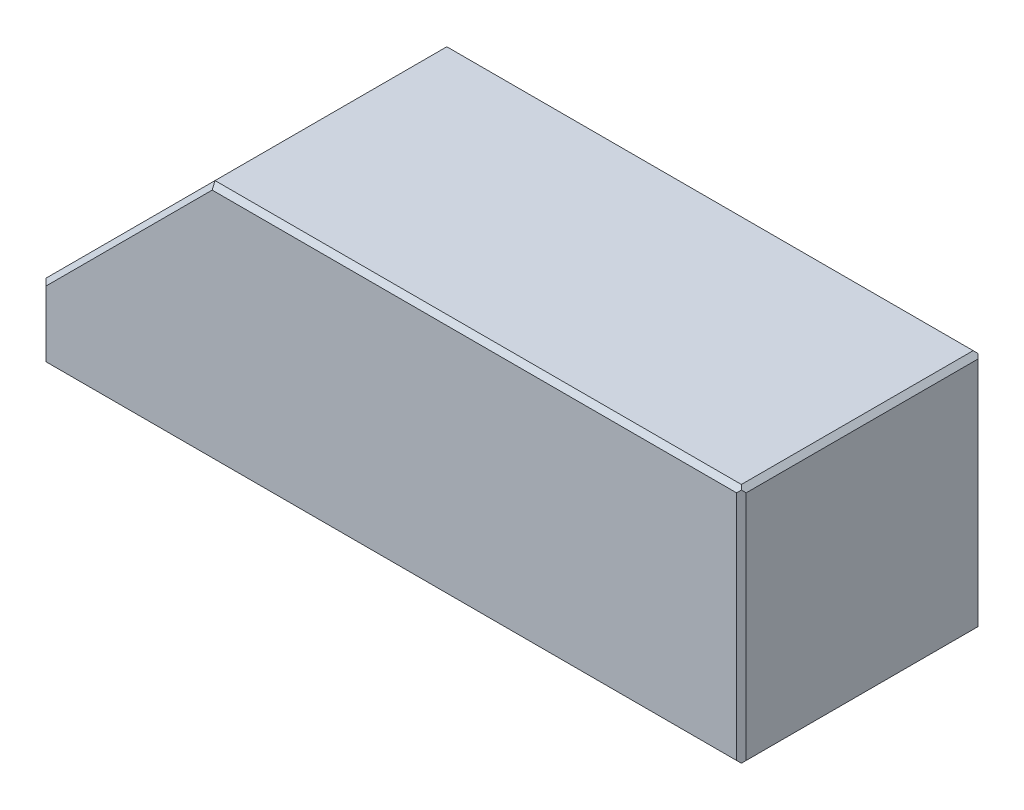
SolidWorks part; units mm, degrees
material "K110"
ref_plane "Front Plane" through (0, 0, 0) normal (0, 0, 1) x (1, 0, 0)
ref_plane "Top Plane" through (0, 0, 0) normal (0, 1, 0) x (1, 0, 0)
ref_plane "Right Plane" through (0, 0, 0) normal (1, 0, 0) x (0, 0, -1)
sketch "Sketch1" plane through (0, 0, 0) normal (0, 0, 1) x (1, 0, 0)
  line L1 (-72.5, -25) -> (72.5, -25)
  line L2 (-72.5, -25) -> (-72.5, 25)
  line L3 (-72.5, 25) -> (72.5, 25)
  line L4 (72.5, -25) -> (72.5, 25)
  line L5 (-72.5, -25) -> (72.5, 25) construction
  line L6 (-72.5, 25) -> (72.5, -25) construction
  point P0 (0, 0)
  dimension "D1" = 50
  dimension "D2" = 145
extrude "Boss-Extrude1" add sketch "Sketch1" along normal mid plane 50
sketch "Sketch2" plane through (0, 0, 0) normal (0, 0, 1) x (1, 0, 0)
  line L0 (-72.5, -10) -> (-37.5, 25)
  line L1 (-72.5, 25) -> (-72.5, -25) construction
  line L2 (72.5, 25) -> (-72.5, 25) construction
  line L3 (-37.5, 25) -> (-72.5, 25)
  line L4 (-72.5, 25) -> (-72.5, -10)
  dimension "D1" = 45
  dimension "D2" = 35
extrude "Cut-Extrude1" cut sketch "Sketch2" against normal through all both and the other way through all
hole_wizard "Ø12.0 (12) Diameter Hole1" positions "Sketch9" profile "Sketch4" hole size "Ø12.0" standard "ISO"
sketch "Sketch9" plane through (-72.5, 0, 0) normal (-1, 0, 0) x (0, 0, 1)
  line L0 (25, -25) -> (-25, -25) construction
  point P0 (0, -5)
  dimension "D1" = 20
sketch "Sketch4" plane through (-72.5, -5, 0) normal (0, 1, 0) x (0, 0, 1)
  line L0 (0, 0) -> (0, 18)
  line L1 (0, 18) -> (6, 18)
  line L2 (6, 18) -> (6, 0)
  line L5 (6, 0) -> (0, 0)
  line L10 (0, 18) -> (-6, 18) construction
  line L11 (0, -6.35) -> (0, 107.95) construction
  dimension "Hole Dia." = 12
  dimension "Hole Depth" = 18
  dimension "Drill Angle" = 180
hole_wizard "M10 Tapped Hole2" positions "Sketch12" profile "Sketch11" tap size "M10" standard "ISO"
sketch "Sketch12" plane through (-54.5, 0, 0) normal (-1, 0, 0) x (0, 0, 1)
  point P0 (0, -5)
sketch "Sketch11" plane through (-54.5, -5, 0) normal (0, 1, 0) x (0, 0, 1)
  line L0 (0, 0) -> (0, 27.5)
  line L1 (0, 27.5) -> (4.25, 24.9463)
  line L2 (4.25, 24.9463) -> (4.25, 0)
  line L5 (4.25, 0) -> (0, 0)
  line L10 (0, 27.5) -> (-4.25, 24.9463) construction
  line L11 (0, -6.35) -> (0, 107.95) construction
  dimension "Tap Drill Dia." = 8.5
  dimension "Tap Drill Depth" = 27.5
  dimension "Drill Angle" = 118
cosmetic thread "Hole Thread3" parameters "D1"=20, "D2"=10
chamfer "Chamfer1" distance 1 angle 45 10 edges at (-72.5, -17.5, -25) (0, -25, -25) (72.5, 0, -25) (17.5, 25, -25) (-55, 7.5, -25) (72.5, 0, 25) (0, -25, 25) (-72.5, -17.5, 25) (-55, 7.5, 25) (17.5, 25, 25)
chamfer "Chamfer2" distance 1 angle 45 2 edges at (72.5, -25, 0) (72.5, 25, 0)
chamfer "Chamfer3" distance 1 angle 45 1 edges at (-72.5, -25, 0)
